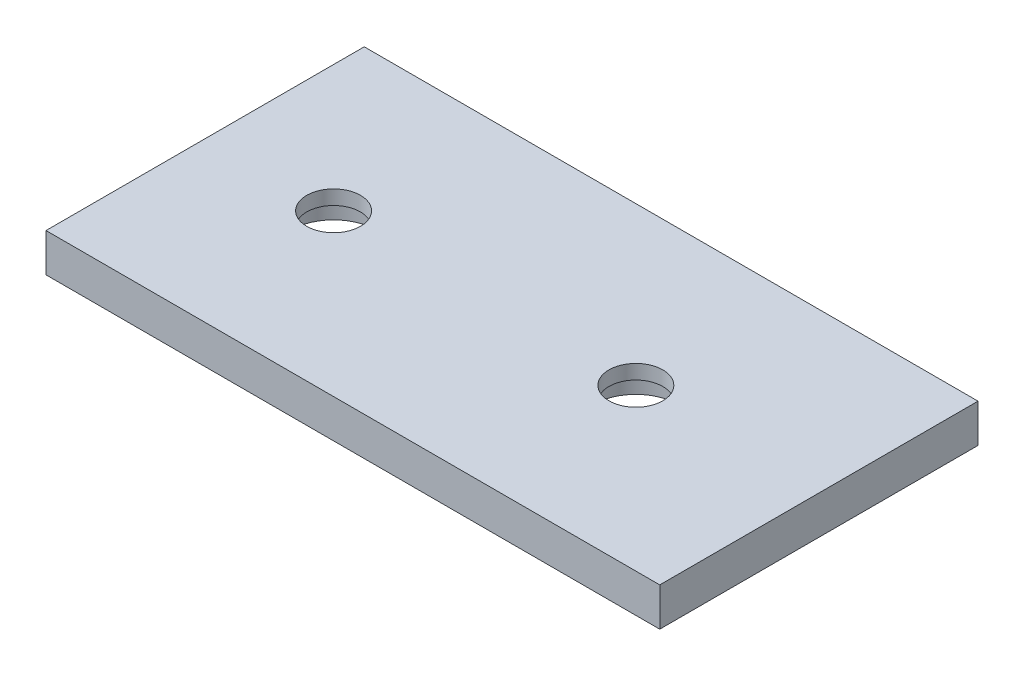
SolidWorks part; units mm, degrees
ref_plane "Front Plane" through (0, 0, 0) normal (0, 0, 1) x (1, 0, 0)
ref_plane "Top Plane" through (0, 0, 0) normal (0, 1, 0) x (1, 0, 0)
ref_plane "Right Plane" through (0, 0, 0) normal (1, 0, 0) x (0, 0, -1)
sketch "Sketch1" plane through (0, 0, 0) normal (0, 1, 0) x (1, 0, 0)
  line L0 (-100, 0) -> (0, 0)
  line L2 (-141.9214, 52.0636) -> (61.1265, 52.0636)
  line L3 (-141.9214, 52.0636) -> (-141.9214, -53.2205)
  line L4 (-141.9214, -53.2205) -> (61.1265, -53.2205)
  line L5 (61.1265, 52.0636) -> (61.1265, -53.2205)
  circle A0 centre (0, 0) radius 14.2875 construction
  circle A1 centre (-100, 0) radius 8.89
  circle A2 centre (0, 0) radius 20.32 construction
  circle A3 centre (0, 0) radius 30.48 construction
  circle A4 centre (-100, 0) radius 14.2875 construction
  circle A5 centre (0, 0) radius 8.89
  dimension "D1" = 28.575
  dimension "D2" = 17.78
  dimension "D4" = 40.64
  dimension "D5" = 60.96
  dimension "D6" = 28.575
  dimension "D7" = 17.78
  dimension "D3" = 100
extrude "Boss-Extrude1" add sketch "Sketch1" along normal blind 12.7
sketch "Sketch2" plane through (0, 0, 0) normal (0, 1, 0) x (1, 0, 0)
  circle A0 centre (-100, 0) radius 14.2875
  circle A1 centre (0, 0) radius 14.2875
  dimension "D1" = 28.575
  dimension "D2" = 28.575
extrude "Cut-Extrude1" cut sketch "Sketch2" along normal blind 7.9375
